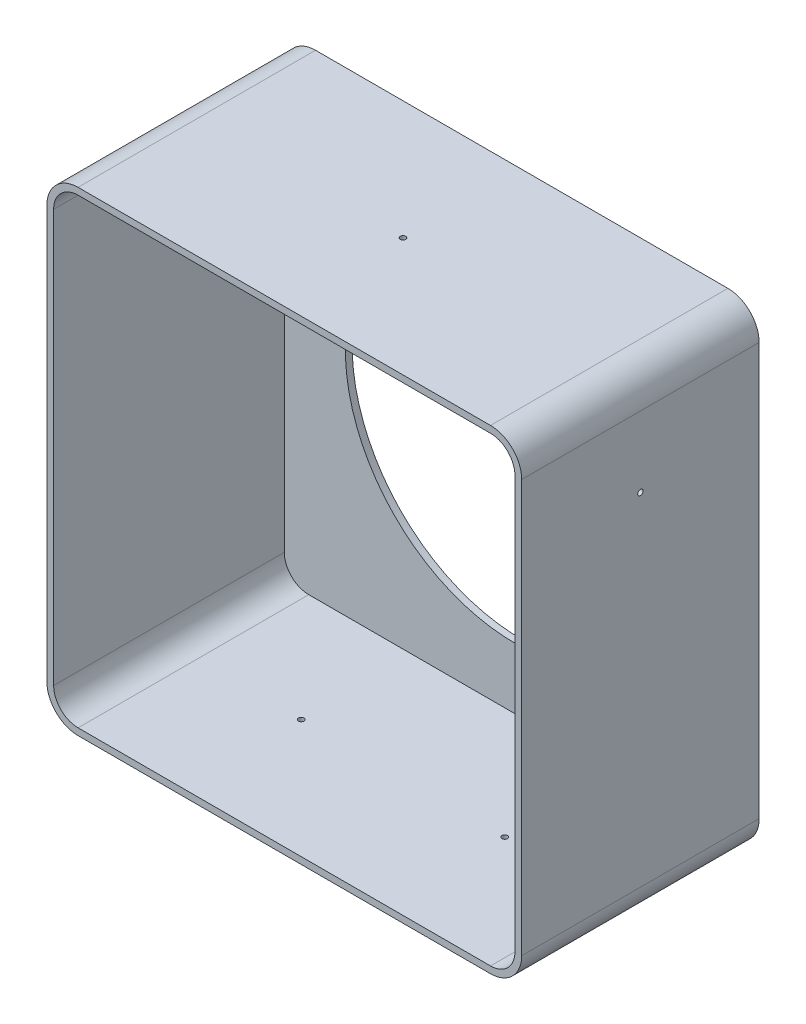
SolidWorks part; units mm, degrees
ref_plane "Front Plane" through (0, 0, 0) normal (0, 0, 1) x (1, 0, 0)
ref_plane "Top Plane" through (0, 0, 0) normal (0, 1, 0) x (1, 0, 0)
ref_plane "Right Plane" through (0, 0, 0) normal (1, 0, 0) x (0, 0, -1)
sketch "Sketch1" plane through (0, 0, 0) normal (0, 0, 1) x (1, 0, 0)
  line L0 (-25, 0) -> (25, 0) construction
  line L2 (-30.3957, 35) -> (30.3957, 35)
  line L3 (-35, 30.3957) -> (-35, -30.3957)
  line L4 (-30.3957, -35) -> (30.3957, -35)
  line L5 (35, 30.3957) -> (35, -30.3957)
  circle A0 centre (0, 0) radius 25
  arc A1 (-30.3957, 35) -> (-35, 30.3957) centre (-30.3957, 30.3957) ccw
  arc A2 (35, -30.3957) -> (30.3957, -35) centre (30.3957, -30.3957) cw
  arc A3 (35, 30.3957) -> (30.3957, 35) centre (30.3957, 30.3957) ccw
  arc A4 (-30.3957, -35) -> (-35, -30.3957) centre (-30.3957, -30.3957) cw
  dimension "D1" = 50
  dimension "D2" = 70
  dimension "D3" = 70
extrude "Boss-Extrude1" add sketch "Sketch1" along normal blind 35
sketch "Sketch2" plane through (0, 0, 35) normal (0, 0, 1) x (1, 0, 0)
  line L8 (-30.3957, -34) -> (30.3957, -34)
  line L9 (34, -30.3957) -> (34, 30.3957)
  line L10 (30.3957, 34) -> (-30.3957, 34)
  line L11 (-34, 30.3957) -> (-34, -30.3957)
  line L12 (-30.3957, -34) -> (30.3957, -34)
  line L13 (34, -30.3957) -> (34, 30.3957)
  line L14 (30.3957, 34) -> (-30.3957, 34)
  line L15 (-34, 30.3957) -> (-34, -30.3957)
  arc A8 (-34, -30.3957) -> (-30.3957, -34) centre (-30.3957, -30.3957) ccw
  arc A9 (30.3957, -34) -> (34, -30.3957) centre (30.3957, -30.3957) ccw
  arc A10 (34, 30.3957) -> (30.3957, 34) centre (30.3957, 30.3957) ccw
  arc A11 (-30.3957, 34) -> (-34, 30.3957) centre (-30.3957, 30.3957) ccw
  arc A12 (-34, -30.3957) -> (-30.3957, -34) centre (-30.3957, -30.3957) ccw
  arc A13 (30.3957, -34) -> (34, -30.3957) centre (30.3957, -30.3957) ccw
  arc A14 (34, 30.3957) -> (30.3957, 34) centre (30.3957, 30.3957) ccw
  arc A15 (-30.3957, 34) -> (-34, 30.3957) centre (-30.3957, 30.3957) ccw
  dimension "D1" = 1
extrude "Cut-Extrude1" cut sketch "Sketch2" against normal blind 34 contours A12 L12 A13 L13 A14 L14 A15 L15
sketch "Sketch3" plane through (35, 0, 0) normal (1, 0, 0) x (0, 0, -1)
  line L0 (-17.5, 20) -> (-17.1, 20) construction
  line L6 (-17.5, 20) -> (-17.5, 35) construction
  line L7 (-35, 35) -> (0, 35) construction
  circle A0 centre (-17.5, 20) radius 0.4
  dimension "D1" = 0.4
  dimension "D2" = 15
extrude "Cut-Extrude2" cut sketch "Sketch3" against normal blind 78
sketch "Sketch4" plane through (0, 35, 0) normal (0, 1, 0) x (1, 0, 0)
  line L0 (-30.3957, 0) -> (30.3957, -35) construction
  circle A0 centre (0, -17.5) radius 0.4
extrude "Cut-Extrude3" cut sketch "Sketch4" against normal blind 22
sketch "Sketch5" plane through (0, -35, 0) normal (0, -1, 0) x (1, 0, 0)
  line L0 (-30.3957, 35) -> (30.3957, 0) construction
  line L1 (-30.3957, 0) -> (30.3957, 35) construction
  line L2 (-35, 17.5) -> (-15, 17.5) construction
  line L4 (-35, 35) -> (-35, 0) construction
  line L6 (35, 17.5) -> (15, 17.5) construction
  line L7 (35, 35) -> (35, 0) construction
  circle A0 centre (-15, 17.5) radius 0.4
  circle A1 centre (15, 17.5) radius 0.4
  point P20 (0, 0)
  point P21 (0, 0)
  dimension "D1" = 20
  dimension "D2" = 20
extrude "Cut-Extrude4" cut sketch "Sketch5" against normal blind 10
